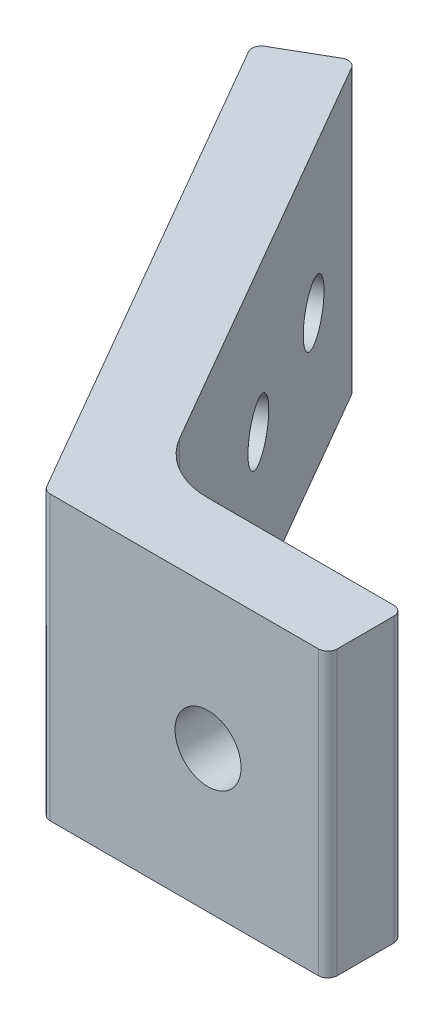
SolidWorks part; units mm, degrees
ref_plane "Спереди" through (0, 0, 0) normal (0, 0, 1) x (1, 0, 0)
ref_plane "Сверху" through (0, 0, 0) normal (0, 1, 0) x (1, 0, 0)
ref_plane "Справа" through (0, 0, 0) normal (1, 0, 0) x (0, 0, -1)
sketch "Эскиз1" plane through (0, 0, 0) normal (0, 1, 0) x (1, 0, 0)
  line L0 (-15, 25.9808) -> (0, 0)
  line L1 (-15, 25.9808) -> (-11.5359, 27.9808)
  line L2 (-11.5359, 27.9808) -> (2.3094, 4)
  line L3 (2.3094, 4) -> (15, 4)
  line L4 (15, 4) -> (15, 0)
  line L5 (0, 0) -> (15, 0)
  dimension "D1" = 15
  dimension "D2" = 120
  dimension "D3" = 30
  dimension "D4" = 4
  dimension "D5" = 4
extrude "Бобышка-Вытянуть1" add sketch "Эскиз1" along normal blind 15
sketch "Эскиз2" plane through (3.4641, 0, -2) normal (0.866, 0, -0.5) x (-0.5, 0, -0.866)
  line L0 (30, 15) -> (30, 0) construction
  circle A0 centre (24, 7.5) radius 1.5
  point P2 (0, 0)
  point P5 (30, 7.5)
  dimension "D1" = 3
  dimension "D2" = 6
extrude "Вырез-Вытянуть1" cut sketch "Эскиз2" against normal blind 15
pattern_linear "Линейный массив1" count 3 spacing 8 along (0.5, 0, 0.866) of "Вырез-Вытянуть1"
sketch "Эскиз3" plane through (0, 0, -4) normal (0, 0, -1) x (-1, 0, 0)
  line L0 (-15, 15) -> (-2.3094, 15) construction
  line L1 (-15, 15) -> (-15, 0) construction
  circle A0 centre (-8.6547, 7.5) radius 1.75
  point P2 (0, 0)
  point P5 (-8.6547, 15)
  point P6 (0, 0)
  point P9 (-15, 7.5)
  dimension "D1" = 3.5
extrude "Вырез-Вытянуть2" cut sketch "Эскиз3" against normal blind 15
fillet "Скругление1" radius 4 1 edges at (2.3094, 7.5, -4)
fillet "Скругление2" radius 0.5 5 edges at (-11.5359, 7.5, -27.9808) (-15, 7.5, -25.9808) (0, 7.5, 0) (15, 7.5, 0) (15, 7.5, -4)
